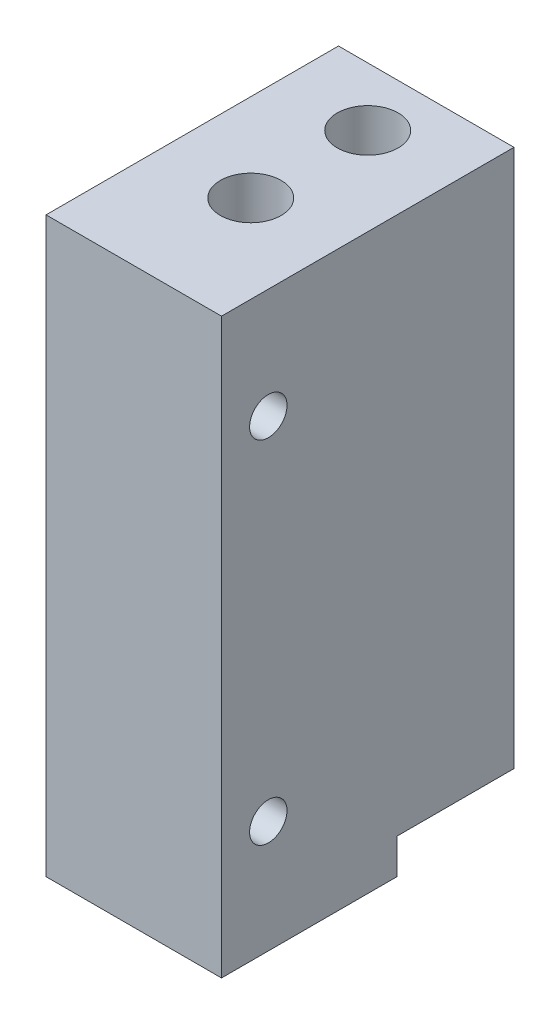
SolidWorks part; units mm, degrees
ref_plane "Front Plane" through (0, 0, 0) normal (0, 0, 1) x (1, 0, 0)
ref_plane "Top Plane" through (0, 0, 0) normal (0, 1, 0) x (1, 0, 0)
ref_plane "Right Plane" through (0, 0, 0) normal (1, 0, 0) x (0, 0, -1)
sketch "Sketch1" plane through (0, 0, 0) normal (1, 0, 0) x (0, 0, -1)
  line L0 (-11, 49) -> (-11, 0) construction
  line L1 (0, 0) -> (-15, 0)
  line L2 (0, 0) -> (0, 49)
  line L3 (0, 49) -> (-15, 49)
  line L4 (-15, 0) -> (-15, 49)
  line L5 (-11, 39.6) -> (-11, 9.6) construction
  circle A0 centre (-11, 39.6) radius 1.6
  circle A1 centre (-11, 9.6) radius 1.6
  point P11 (-11, 38.5742)
  dimension "D4" = 3.2
  dimension "D5" = 30
  dimension "D6" = 9.6
  dimension "D1" = 15
  dimension "D2" = 49
  dimension "D3" = 11
extrude "Boss-Extrude1" add sketch "Sketch1" along normal blind 15
sketch "Sketch2" plane through (0, 0, 0) normal (0, -1, 0) x (1, 0, 0)
  line L0 (0, 5) -> (15, 5) construction
  line L1 (0, 15) -> (0, 0) construction
  line L2 (15, 15) -> (15, 0) construction
  line L4 (15, 0) -> (0, 0) construction
  circle A2 centre (7.5, 5) radius 2.6
  dimension "D1" = 5.2
  dimension "D5" = 5
extrude "Cut-Extrude1" cut sketch "Sketch2" against normal through all
sketch "Sketch5" plane through (0, 0, 0) normal (0, 0, -1) x (-1, 0, 0)
  line L0 (0, 0) -> (0, 49) construction
  line L1 (-15, 49) -> (0, 49)
  line L2 (-15, 49) -> (-15, 3)
  line L3 (-15, 3) -> (0, 3)
  line L4 (0, 49) -> (0, 3)
  dimension "D1" = 46
extrude "Boss-Extrude3" add sketch "Sketch5" along normal blind 10
sketch "Sketch6" plane through (0, 3, 0) normal (0, -1, 0) x (1, 0, 0)
  line L0 (7.5, 5) -> (7.5, -10) construction
  line L1 (15, -10) -> (0, -10) construction
  circle A0 centre (7.5, -5) radius 2.6
  circle A1 centre (7.5, 5) radius 2.6 construction
  dimension "D1" = 5.2
  dimension "D2" = 10
extrude "Cut-Extrude2" cut sketch "Sketch6" against normal through all
